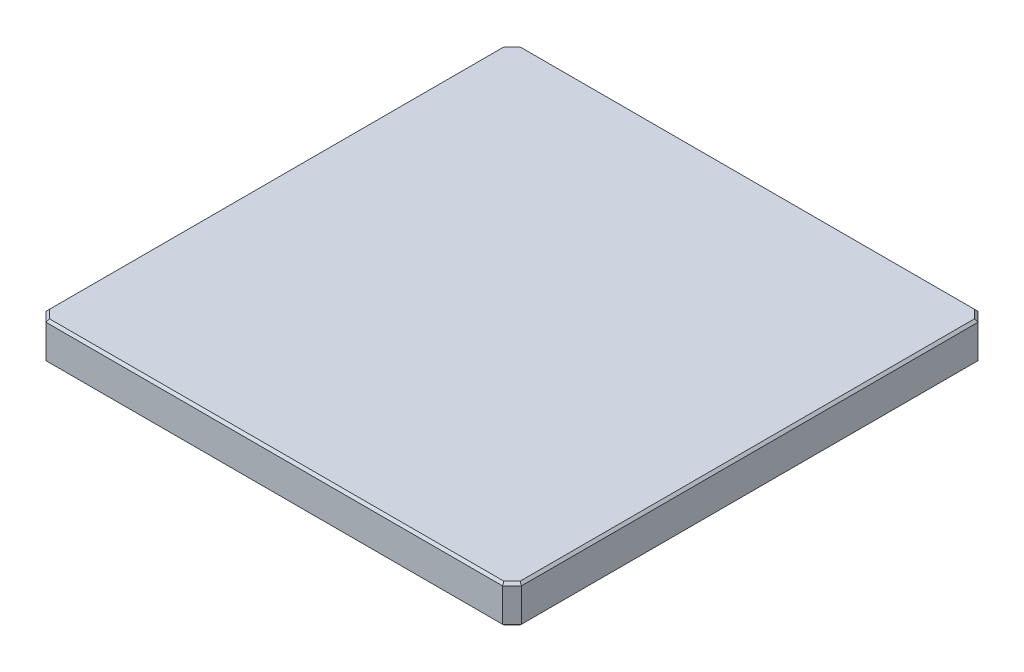
SolidWorks part; units mm, degrees
ref_plane "Front Plane" through (0, 0, 0) normal (0, 0, 1) x (1, 0, 0)
ref_plane "Top Plane" through (0, 0, 0) normal (0, 1, 0) x (1, 0, 0)
ref_plane "Right Plane" through (0, 0, 0) normal (1, 0, 0) x (0, 0, -1)
sketch "Sketch1" plane through (0, 0, 0) normal (0, 0, 1) x (1, 0, 0)
  line L0 (-50, 0) -> (-50, 8)
  line L1 (-50, 0) -> (50, 0)
  line L2 (0, 0) -> (0, 8) construction
  line L3 (-50, 8) -> (50, 8)
  line L4 (50, 0) -> (50, 8)
  dimension "D1" = 8
  dimension "D2" = 50
extrude "Boss-Extrude1" add sketch "Sketch1" along normal blind 100
chamfer "Chamfer1" distance 2 angle 45 4 edges at (-50, 4, 0) (50, 4, 0) (-50, 4, 100) (50, 4, 100)
chamfer "Chamfer2" distance 0.5 angle 45 16 edges at (-49, 0, 99) (0, 0, 100) (49, 0, 99) (50, 0, 50) (49, 0, 1) (0, 0, 0) (-49, 0, 1) (-50, 0, 50) (49, 8, 1) (50, 8, 50) (49, 8, 99) (0, 8, 100) (-49, 8, 99) (-50, 8, 50) (-49, 8, 1) (0, 8, 0)
